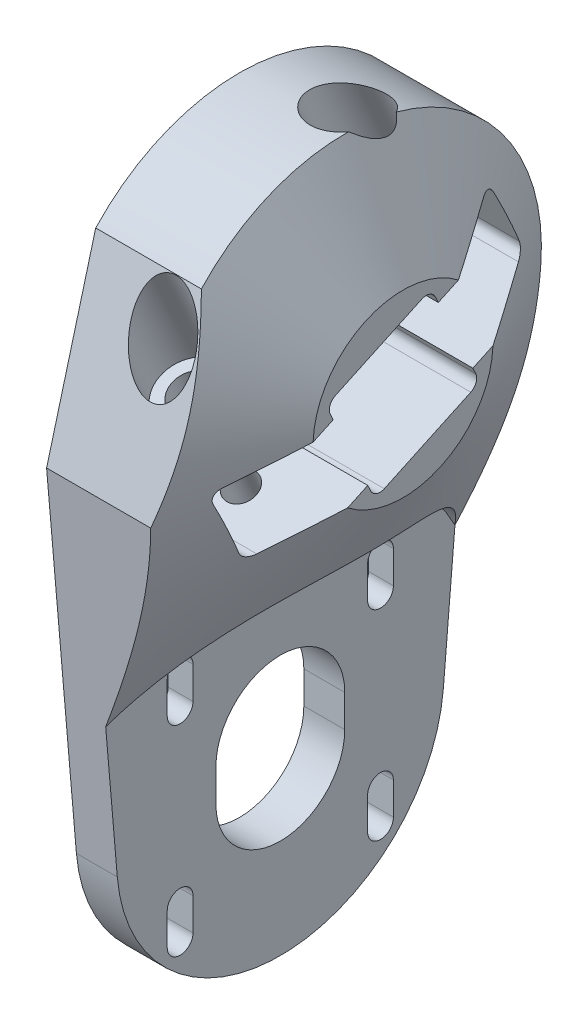
SolidWorks part; units mm, degrees
ref_plane "Front Plane" through (0, 0, 0) normal (0, 0, 1) x (1, 0, 0)
ref_plane "Top Plane" through (0, 0, 0) normal (0, 1, 0) x (1, 0, 0)
ref_plane "Right Plane" through (0, 0, 0) normal (1, 0, 0) x (0, 0, -1)
sketch "Sketch1" plane through (0, 0, 0) normal (1, 0, 0) x (0, 0, -1)
  line L0 (4.3532, 11.9603) -> (-11.9603, 4.3532)
  line L1 (4.3532, 11.9603) -> (11.9603, -4.3532)
  line L2 (-11.9603, 4.3532) -> (-4.3532, -11.9603)
  line L3 (11.9603, -4.3532) -> (-4.3532, -11.9603)
  line L4 (4.3532, 11.9603) -> (-4.3532, -11.9603) construction
  line L5 (-11.9603, 4.3532) -> (11.9603, -4.3532) construction
  line L6 (0, 0) -> (0, -57.15) construction
  line L7 (-30.3693, -2.5958) -> (-25.3077, -61.8132)
  line L8 (25.3077, -61.8132) -> (30.3693, -2.5958)
  line L9 (0, -57.15) -> (0, -103.9417) construction
  arc A0 (30.3693, -2.5958) -> (-30.3693, -2.5958) centre (0, 0) ccw
  arc A1 (-25.3077, -61.8132) -> (25.3077, -61.8132) centre (0, -59.65) ccw
  dimension "D1" = 2.5
  dimension "D2" = 30.48
  dimension "D6" = 57.15
  dimension "D7" = 25.4
  dimension "D8" = 0
  dimension "D3" = 18
  dimension "D4" = 18
  dimension "D5" = 25
extrude "Boss-Extrude1" add sketch "Sketch1" along normal blind 6.35
sketch "Sketch19" plane through (6.35, 0, 0) normal (1, 0, 0) x (0, 0, -1)
  line L0 (0, -59.65) -> (0, -54.65)
  line L1 (0, -54.65) -> (15.5563, -39.0937) construction
  line L2 (15.5563, -44.0937) -> (15.5563, -39.0937) construction
  line L3 (13.5563, -44.0937) -> (13.5563, -39.0937)
  line L4 (17.5563, -44.0937) -> (17.5563, -39.0937)
  line L5 (-10, -59.65) -> (-10, -54.65)
  line L6 (10, -59.65) -> (10, -54.65)
  line L7 (0, -57.15) -> (7.4061, -57.15) construction
  line L8 (15.5563, -44.0937) -> (0, -59.65) construction
  line L9 (17.5563, -70.2063) -> (17.5563, -75.2063)
  line L10 (13.5563, -70.2063) -> (13.5563, -75.2063)
  line L11 (-17.5563, -44.0937) -> (-17.5563, -39.0937)
  line L12 (-13.5563, -44.0937) -> (-13.5563, -39.0937)
  line L13 (-13.5563, -70.2063) -> (-13.5563, -75.2063)
  line L14 (-17.5563, -70.2063) -> (-17.5563, -75.2063)
  line L15 (-15.5563, -44.0937) -> (0, -59.65) construction
  line L16 (0, -59.65) -> (-15.5563, -75.2063) construction
  line L17 (0, -59.65) -> (15.5563, -75.2063) construction
  arc A0 (-25.3077, -61.8132) -> (25.3077, -61.8132) centre (0, -59.65) ccw construction
  arc A1 (-25.3077, -61.8132) -> (25.3077, -61.8132) centre (0, -59.65) ccw
  arc A2 (-10, -59.65) -> (10, -59.65) centre (0, -59.65) ccw
  arc A3 (17.5563, -75.2063) -> (13.5563, -75.2063) centre (15.5563, -75.2063) cw
  arc A4 (13.5563, -70.2063) -> (17.5563, -70.2063) centre (15.5563, -70.2063) cw
  arc A6 (17.5563, -39.0937) -> (13.5563, -39.0937) centre (15.5563, -39.0937) ccw
  arc A7 (13.5563, -44.0937) -> (17.5563, -44.0937) centre (15.5563, -44.0937) ccw
  arc A8 (-17.5563, -39.0937) -> (-13.5563, -39.0937) centre (-15.5563, -39.0937) cw
  arc A9 (10, -54.65) -> (-10, -54.65) centre (0, -54.65) ccw
  arc A10 (-13.5563, -44.0937) -> (-17.5563, -44.0937) centre (-15.5563, -44.0937) cw
  arc A11 (-13.5563, -70.2063) -> (-17.5563, -70.2063) centre (-15.5563, -70.2063) ccw
  arc A13 (-17.5563, -75.2063) -> (-13.5563, -75.2063) centre (-15.5563, -75.2063) ccw
  point P8 (0, -57.15)
  dimension "D1" = 135
  dimension "D3" = 22
  dimension "D5" = 4
  dimension "D6" = 5
  dimension "D4" = 4
  dimension "D8" = 0
  dimension "D2" = 5
  dimension "D7" = 45
extrude "Cut-Extrude18" cut sketch "Sketch19" against normal blind 10
sketch "Sketch20" plane through (6.35, 0, 0) normal (1, 0, 0) x (0, 0, -1)
  circle A0 centre (0, 0) radius 57.15
  arc A1 (-25.3077, -61.8132) -> (25.3077, -61.8132) centre (0, -59.65) ccw construction
  point P3 (0, -85.05)
extrude "Boss-Extrude5" add sketch "Sketch20" along normal blind 19.05
sketch "Sketch21" plane through (0, 0, 0) normal (-1, 0, 0) x (0, 0, 1)
  line L0 (-24.435, 4.3878) -> (-10.8404, -1.9515)
  line L1 (11.9603, 4.3532) -> (4.3532, -11.9603) construction
  line L3 (-4.3532, 11.9603) -> (-11.9603, -4.3532) construction
  line L4 (-4.3532, 11.9603) -> (11.9603, 4.3532) construction
  line L5 (11.9603, 4.3532) -> (10.8404, 1.9515)
  line L7 (-4.3532, 11.9603) -> (-5.4731, 9.5586)
  line L8 (-4.3532, 11.9603) -> (11.9603, 4.3532)
  line L9 (-21.7514, 10.1428) -> (-25.3766, 11.8333) construction
  line L10 (19.0678, -15.8979) -> (5.4731, -9.5586)
  line L11 (19.0678, -15.8979) -> (24.435, -4.3878)
  line L12 (-24.435, 4.3878) -> (-19.0678, 15.8979)
  line L13 (24.435, -4.3878) -> (10.8404, 1.9515)
  line L16 (4.3532, -11.9603) -> (5.4731, -9.5586)
  line L17 (-11.9603, -4.3532) -> (-10.8404, -1.9515)
  line L18 (11.9603, 4.3532) -> (-4.3532, 11.9603)
  line L21 (-10.8404, -1.9515) -> (-11.9603, -4.3532)
  line L24 (-10.8404, -1.9515) -> (-24.435, 4.3878)
  line L27 (-5.4731, 9.5586) -> (-4.3532, 11.9603)
  line L29 (-5.4731, 9.5586) -> (-19.0678, 15.8979)
  line L30 (5.4731, -9.5586) -> (4.3532, -11.9603)
  line L31 (10.8404, 1.9515) -> (11.9603, 4.3532)
  line M13 (-11.9603, -4.3532) -> (-4.3532, 11.9603)
  line M14 (-4.3532, 11.9603) -> (11.9603, 4.3532)
  line M15 (11.9603, 4.3532) -> (4.3532, -11.9603)
  line M16 (4.3532, -11.9603) -> (-11.9603, -4.3532)
  dimension "D1" = 15
  dimension "D2" = 12.7
extrude "Cut-Extrude14" cut sketch "Sketch21" against normal through all contours L29 L12 L0 M13 | M13 M16 M15 M14 | L11 L13 L10 M15
sketch "Sketch22" plane through (0, 5.7551, 2.6836) normal (0, -0.9063, -0.4226) x (-1, 0, 0)
  line L0 (-25.4, -9) -> (0, -9) construction
  line L2 (0, -28.6209) -> (0, 30.48) construction
  circle A0 centre (-12.5, -16.5) radius 3.175
  dimension "D2" = 12.5
  dimension "D3" = 6.35
  dimension "D1" = 7.5
extrude "Cut-Extrude15" cut sketch "Sketch22" against normal through all
ref_plane "Plane1" through (0, 10.3591, 4.8305) normal (0, -0.9063, -0.4226) x (-1, 0, 0)
sketch "Sketch24" plane through (0, 10.3591, 4.8305) normal (0, -0.9063, -0.4226) x (-1, 0, 0)
  circle A0 centre (-12.5, -16.5) radius 5
  dimension "D1" = 10
extrude "Cut-Extrude16" cut sketch "Sketch24" against normal through all
sketch "Sketch25" plane through (0, -5.7551, -2.6836) normal (0, 0.9063, 0.4226) x (1, 0, 0)
  circle A0 centre (12.5, -16.5) radius 3.175 construction
  circle A1 centre (12.5, -16.5) radius 3.175
  circle A2 centre (12.5, -16.5) radius 2.3813
  dimension "D1" = 0.7937
extrude "Cut-Extrude17" cut sketch "Sketch25" against normal blind 10 contours A2
ref_plane "Plane2" through (0, 0, 0) normal (0, 0.4226, -0.9063) x (-1, 0, 0)
mirror "Mirror1" about plane through (0, 0, 0) normal (0, 0.4226, -0.9063) of "Cut-Extrude17", "Cut-Extrude15", "Cut-Extrude16"
mirror "Mirror2" about plane through (0, 0, 0) normal (1, 0, 0) of bodies 124 126
delete or keep bodies "Body-Delete/Keep 1" type delete bodies bodies 127
chamfer "Chamfer2" distance 2.5 angle 45 8 edges at (0, -46.0937, 15.5563) (0, -41.5937, 13.5563) (0, -37.0937, 15.5563) (0, -41.5937, 17.5563) (0, -46.0937, -15.5563) (0, -41.5937, -17.5563) (0, -41.5937, -13.5563) (0, -37.0937, -15.5563)
sketch "Sketch26" plane through (0, 0, 0) normal (-1, 0, 0) x (0, 0, 1)
  line L0 (11.4538, -58.2291) -> (27.0119, -8.4408)
  line L1 (0, 0) -> (0, -54.65) construction
  circle A0 centre (0, -54.65) radius 12
  circle A1 centre (0, 0) radius 28.3
  dimension "D1" = 24
  dimension "D2" = 56.6
fillet "Fillet1" radius 1.5875 8 edges at (12.7, 4.3878, -24.435) (12.7, 15.8979, -19.0678) (12.7, -4.3878, 24.435) (12.7, -15.8979, 19.0678) (12.7, 11.9603, -4.3532) (12.7, 4.3532, 11.9603) (12.7, -11.9603, 4.3532) (12.7, -4.3532, -11.9603)
sketch "Sketch28" plane through (6.35, 0, 0) normal (1, 0, 0) x (0, 0, -1)
  arc A0 (-10, -54.65) -> (10, -54.65) centre (0, -54.65) ccw construction
  arc A1 (-10, -54.65) -> (10, -54.65) centre (0, -54.65) ccw
  circle A3 centre (0, -54.65) radius 30.48
extrude "Cut-Extrude19" cut sketch "Sketch28" along normal through all contours A3
sketch "Sketch29" plane through (25.4, 0, 0) normal (1, 0, 0) x (0, 0, -1)
  arc A1 (30.3693, -2.5958) -> (-30.3693, -2.5958) centre (0, 0) ccw construction
  arc A2 (30.3693, -2.5958) -> (-30.3693, -2.5958) centre (0, 0) ccw
  circle A3 centre (0, 0) radius 13.97
sketch "Sketch30" plane through (6.35, 0, 0) normal (1, 0, 0) x (0, 0, -1)
  circle A0 centre (0, 0) radius 48.9194
sketch "Sketch31" plane through (0, 0, 0) normal (0, 1, 0) x (1, 0, 0)
  line L0 (25.4, -13.97) -> (25.4, 13.97) construction
  line L1 (25.4, -13.97) -> (25.4, 13.97)
  line L2 (6.35, -48.9194) -> (6.35, 48.9194) construction
  line L3 (6.35, -48.9194) -> (6.35, 48.9194)
  line L4 (25.4, -13.97) -> (6.35, -48.9194)
  line L5 (6.35, -48.9194) -> (6.35, -59.9521)
  line L6 (6.35, -59.9521) -> (25.4, -59.9521)
  line L7 (25.4, -59.9521) -> (25.4, -13.97)
  line L8 (25.4, 0) -> (0, 0) construction
revolve "Cut-Revolve1" cut sketch "Sketch31" angle 360 about L8
sketch "Sketch32" plane through (6.35, 0, 0) normal (-1, 0, 0) x (0, 0, 1)
  line L0 (30.3693, -2.5958) -> (25.3077, -61.8132) construction
  line L1 (-25.3077, -61.8132) -> (-30.3693, -2.5958) construction
  line L2 (30.3693, -2.5958) -> (25.3077, -61.8132)
  line L3 (-25.3077, -61.8132) -> (-30.3693, -2.5958)
  arc A0 (30.3693, -2.5958) -> (-30.3693, -2.5958) centre (0, 0) ccw construction
  arc A1 (30.3693, -2.5958) -> (-30.3693, -2.5958) centre (0, 0) ccw
  circle A2 centre (0, 0) radius 48.9194 construction
  circle A3 centre (0, 0) radius 48.9194
  arc M2 (27.1106, -40.72) -> (-27.1106, -40.72) centre (0, 0) ccw
  line M3 (-27.1106, -40.72) -> (-30.3693, -2.5958)
  arc M4 (-30.3693, -2.5958) -> (30.3693, -2.5958) centre (0, 0) cw
  line M5 (30.3693, -2.5958) -> (27.1106, -40.72)
extrude "Cut-Extrude20" cut sketch "Sketch32" against normal through all contours M5 M2 M3 M4
sketch "Sketch33" plane through (0, 0, 0) normal (-1, 0, 0) x (0, 0, 1)
  line L0 (30.3693, -2.5958) -> (25.3077, -61.8132) construction
  line L1 (30.3693, -2.5958) -> (25.3077, -61.8132)
  line L2 (29.934, -7.6887) -> (22.3087, 20.769)
  line L3 (22.9962, -3.7169) -> (10.8404, 1.9515) construction
  arc A0 (30.3693, -2.5958) -> (-30.3693, -2.5958) centre (0, 0) ccw construction
  arc A1 (30.3693, -2.5958) -> (-30.3693, -2.5958) centre (0, 0) ccw
  arc M35 (30.3693, -2.5958) -> (-30.3693, -2.5958) centre (0, 0) ccw
  dimension "D1" = 50
  dimension "D2" = 26.924
extrude "Cut-Extrude21" cut sketch "Sketch33" against normal through all contours L2 L1 M35
equation "\".75i\"=14.27"
